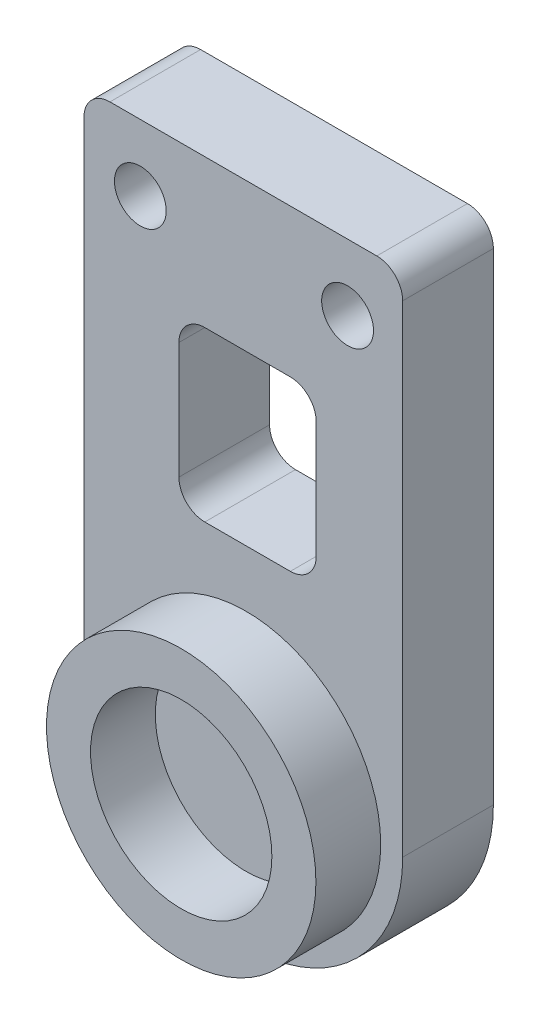
SolidWorks part; units mm, degrees
ref_plane "Front Plane" through (0, 0, 0) normal (0, 0, 1) x (1, 0, 0)
ref_plane "Top Plane" through (0, 0, 0) normal (0, 1, 0) x (1, 0, 0)
ref_plane "Right Plane" through (0, 0, 0) normal (1, 0, 0) x (0, 0, -1)
other "Graphic1"
ref_plane "Plane1" through (0, 0, 8) normal (0, 0, 1) x (1, 0, 0)
sketch "Sketch2" plane through (0, 0, 8) normal (0, 0, 1) x (1, 0, 0)
  line L1 (-301.2546, 240.5057) -> (-288.9546, 240.5057)
  line L2 (-301.2546, 240.5057) -> (-301.2546, 214.9057)
  line L3 (-301.2546, 214.9057) -> (-288.9546, 214.9057)
  line L4 (-288.9546, 240.5057) -> (-288.9546, 214.9057)
  dimension "D1" = 12.3
  dimension "D2" = 25.6
extrude "Boss-Extrude2" add sketch "Sketch2" along normal blind 3.5
sketch "Sketch3" plane through (0, 0, 11.5) normal (0, 0, 1) x (1, 0, 0)
  line L1 (-297.5929, 234.7929) -> (-292.2929, 234.7929)
  line L2 (-297.5929, 234.7929) -> (-297.5929, 228.2929)
  line L3 (-297.5929, 228.2929) -> (-292.2929, 228.2929)
  line L4 (-292.2929, 234.7929) -> (-292.2929, 228.2929)
  circle A0 centre (-299.082, 237.9443) radius 1
  circle A1 centre (-291.082, 237.9443) radius 1
  dimension "D1" = 8
  dimension "D3" = 6.5
  dimension "D4" = 5.3
extrude "Cut-Extrude1" cut sketch "Sketch3" against normal blind 3.5
fillet "Fillet1" radius 1 6 edges at (-292.2929, 228.2929, 9.75) (-297.5929, 228.2929, 9.75) (-297.5929, 234.7929, 9.75) (-292.2929, 234.7929, 9.75) (-301.2546, 240.5057, 9.75) (-288.9546, 240.5057, 9.75)
fillet "Fillet2" radius 6 2 edges at (-288.9546, 214.9057, 9.75) (-301.2546, 214.9057, 9.75)
sketch "Sketch4" plane through (0, 0, 11.5) normal (0, 0, 1) x (1, 0, 0)
  circle A0 centre (-295.0045, 220.9057) radius 3.5
  circle A1 centre (-295.0045, 220.9057) radius 5.2
  dimension "D1" = 7
  dimension "D3" = 10.4
  dimension "D2" = 6
extrude "Boss-Extrude3" add sketch "Sketch4" along normal blind 2.5
